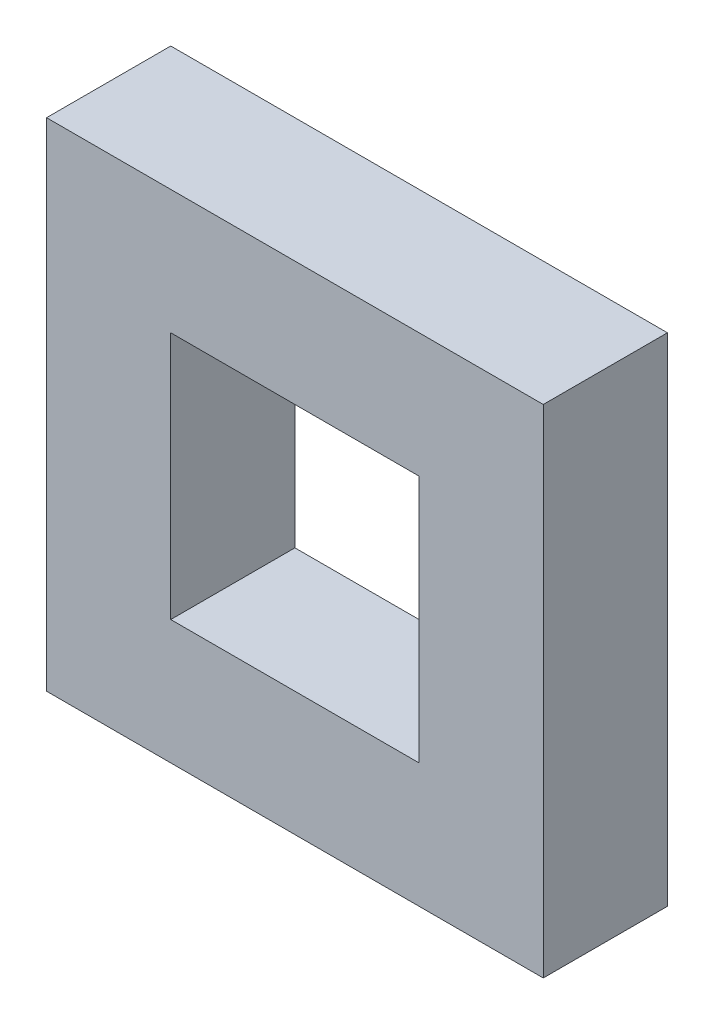
SolidWorks part; units mm, degrees
ref_plane "Front Plane" through (0, 0, 0) normal (0, 0, 1) x (1, 0, 0)
ref_plane "Top Plane" through (0, 0, 0) normal (0, 1, 0) x (1, 0, 0)
ref_plane "Right Plane" through (0, 0, 0) normal (1, 0, 0) x (0, 0, -1)
sketch "Sketch1" plane through (0, 0, 0) normal (0, 0, 1) x (1, 0, 0)
  line L1 (0, 0) -> (20, 0)
  line L2 (0, 0) -> (0, 20)
  line L3 (0, 20) -> (20, 20)
  line L4 (20, 0) -> (20, 20)
  dimension "D1" = 20
extrude "Boss-Extrude1" add sketch "Sketch1" along normal blind 5
sketch "Sketch2" plane through (0, 0, 5) normal (0, 0, 1) x (1, 0, 0)
  line L0 (0, 20) -> (20, 0) construction
  line L1 (0, 20) -> (0, 0) construction
  line L2 (0, 0) -> (10, 10) construction
  line L3 (10, 10) -> (20, 20) construction
  line L5 (5, 5) -> (15, 5)
  line L6 (5, 5) -> (5, 15)
  line L7 (5, 15) -> (15, 15)
  line L8 (15, 5) -> (15, 15)
extrude "Cut-Extrude1" cut sketch "Sketch2" against normal through all
